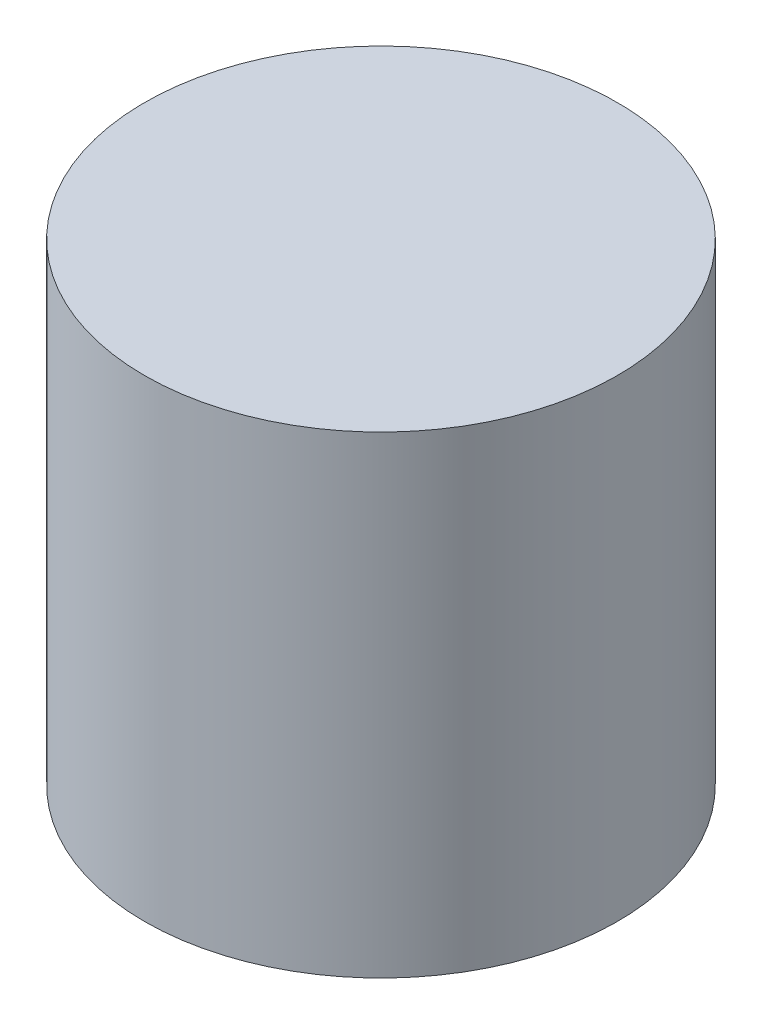
SolidWorks part; units mm, degrees
material "1060-H12"
ref_plane "Спереди" through (0, 0, 0) normal (0, 0, 1) x (1, 0, 0)
ref_plane "Сверху" through (0, 0, 0) normal (0, 1, 0) x (1, 0, 0)
ref_plane "Справа" through (0, 0, 0) normal (1, 0, 0) x (0, 0, -1)
other "Configuration Table"
sketch "Эскиз1" plane through (0, 0, 0) normal (0, 1, 0) x (1, 0, 0)
  circle A0 centre (0, 0) radius 17.5
  dimension "D1" = 35
extrude "Бобышка-Вытянуть1" add sketch "Эскиз1" along normal blind 35
